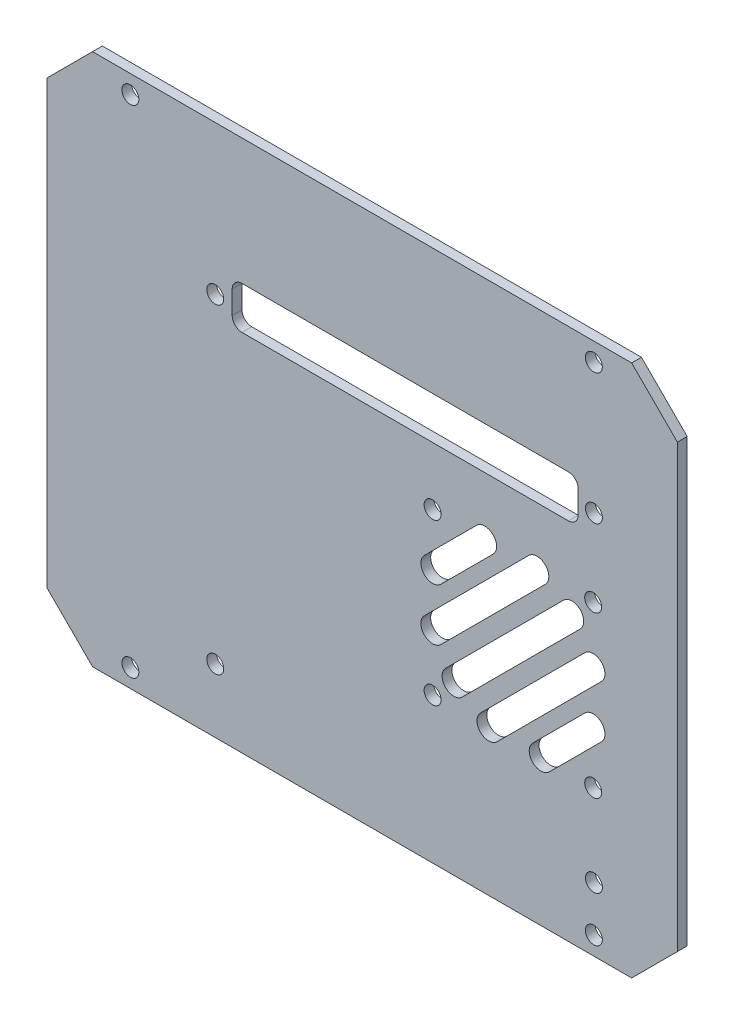
SolidWorks part; units mm, degrees
ref_plane "前视基准面" through (0, 0, 0) normal (0, 0, 1) x (1, 0, 0)
ref_plane "上视基准面" through (0, 0, 0) normal (0, 1, 0) x (1, 0, 0)
ref_plane "右视基准面" through (0, 0, 0) normal (1, 0, 0) x (0, 0, -1)
sketch "草图2" plane through (0, 0, -39.19) normal (0, 0, -1) x (-1, 0, 0)
  line L32 (-47.3467, -34.0538) -> (-40.3426, -41.058)
  line L33 (-40.3426, -41.058) -> (42.2491, -41.058)
  line L34 (42.2491, -41.058) -> (49.2533, -34.0538)
  line L35 (49.2533, -34.0538) -> (49.2533, 33.5378)
  line L36 (49.2533, 33.5378) -> (42.2491, 40.542)
  line L37 (-47.3467, 33.5378) -> (-47.3467, -34.0538)
  line L38 (-40.3426, 40.542) -> (-47.3467, 33.5378)
  line L39 (42.2491, 40.542) -> (-40.3426, 40.542)
  line L40 (-47.3467, -34.0538) -> (-40.3426, -41.058)
  line L41 (-40.3426, -41.058) -> (42.2491, -41.058)
  line L42 (42.2491, -41.058) -> (49.2533, -34.0538)
  line L43 (49.2533, -34.0538) -> (49.2533, 33.5378)
  line L44 (49.2533, 33.5378) -> (42.2491, 40.542)
  line L45 (-47.3467, 33.5378) -> (-47.3467, -34.0538)
  line L46 (-40.3426, 40.542) -> (-47.3467, 33.5378)
  line L47 (42.2491, 40.542) -> (-40.3426, 40.542)
  dimension "D1" = 0.2
extrude "凸台-拉伸1" add sketch "草图2" along normal blind 1.5
sketch "草图3" plane through (0, 0, -40.69) normal (0, 0, -1) x (-1, 0, 0)
  circle A0 centre (-34.5467, -38.258) radius 1.3
  circle A1 centre (36.4533, -38.258) radius 1.3
  circle A2 centre (-34.5467, 37.742) radius 1.3
  circle A3 centre (36.4533, 37.742) radius 1.3
  dimension "D1" = 2.6
extrude "切除-拉伸1" cut sketch "草图3" against normal through all
sketch "草图4" plane through (0, 0, -40.69) normal (0, 0, -1) x (-1, 0, 0)
  circle A1 centre (23.4533, -31.2932) radius 1.3
  circle A2 centre (23.4533, -31.2932) radius 1.3
  circle A3 centre (-34.5583, -31.2932) radius 1.3
  circle A4 centre (-34.5583, -31.2932) radius 1.3
  circle A5 centre (23.4533, 17.742) radius 1.3
  circle A6 centre (23.4533, 17.742) radius 1.3
  circle A7 centre (-34.5583, 17.742) radius 1.3
  circle A8 centre (-34.5583, 17.742) radius 1.3
  dimension "D1" = 0
  dimension "D2" = 0
  dimension "D3" = 0
  dimension "D4" = 0
extrude "切除-拉伸2" cut sketch "草图4" against normal up to next
sketch "草图5" plane through (0, 0, -40.69) normal (0, 0, -1) x (-1, 0, 0)
  line L1 (-32.1467, 14.742) -> (20.8533, 14.742)
  line L2 (-32.1467, 14.742) -> (-32.1467, 21.242)
  line L3 (-32.1467, 21.242) -> (20.8533, 21.242)
  line L4 (20.8533, 14.742) -> (20.8533, 21.242)
  line L7 (-47.3467, 33.5378) -> (-47.3467, -34.0538) construction
  line L9 (42.2491, 40.542) -> (-40.3426, 40.542) construction
  dimension "D1" = 53
  dimension "D2" = 6.5
  dimension "D3" = 15.2
  dimension "D4" = 19.3
extrude "切除-拉伸3" cut sketch "草图5" against normal up to next
fillet "圆角1" radius 1.5 4 edges at (32.1467, 21.242, -39.94) (32.1467, 14.742, -39.94) (-20.8533, 14.742, -39.94) (-20.8533, 21.242, -39.94)
sketch "草图7" plane through (0, 0, -40.69) normal (0, 0, -1) x (-1, 0, 0)
  circle A0 centre (-34.4467, 5.842) radius 1.3
  circle A1 centre (-34.4467, -18.758) radius 1.3
  circle A2 centre (-9.8467, 5.842) radius 1.3
  circle A3 centre (-9.8467, -18.758) radius 1.3
  circle A4 centre (-34.5583, 17.742) radius 1.3 construction
extrude "切除-拉伸4" cut sketch "草图7" against normal up to next
sketch "草图8" plane through (0, 0, -40.69) normal (0, 0, -1) x (-1, 0, 0)
  line L0 (-34.4467, 5.842) -> (-9.8467, -18.758) construction
  line L1 (-34.4467, 5.842) -> (-9.8467, 5.842) construction
  line L2 (-34.4467, 5.842) -> (-34.4467, -18.758) construction
  line L3 (-34.4467, -18.758) -> (-9.8467, -18.758) construction
  line L4 (-9.8467, 5.842) -> (-9.8467, -18.758) construction
  line L5 (-31.194, 2.5893) -> (-13.0994, -15.5053) construction
  line L6 (-29.9212, 3.8621) -> (-11.8266, -14.2325)
  line L7 (-32.4668, 1.3165) -> (-14.3722, -16.7781)
  line L8 (-34.4467, -2.758) -> (-18.4467, -18.758) construction
  line L9 (-33.1739, -1.4852) -> (-17.1739, -17.4852)
  line L10 (-35.7195, -4.0308) -> (-19.7195, -20.0308)
  line L11 (-25.8467, 5.842) -> (-9.8467, -10.158) construction
  line L12 (-24.5739, 7.1148) -> (-8.5739, -8.8852)
  line L13 (-27.1195, 4.5692) -> (-11.1195, -11.4308)
  line L14 (-17.8467, 5.842) -> (-9.8467, -2.158) construction
  line L15 (-16.5739, 7.1148) -> (-8.5739, -0.8852)
  line L16 (-19.1195, 4.5692) -> (-11.1195, -3.4308)
  line L17 (-34.4467, -10.758) -> (-26.4467, -18.758) construction
  line L18 (-33.1739, -9.4852) -> (-25.1739, -17.4852)
  line L19 (-35.7195, -12.0308) -> (-27.7195, -20.0308)
  arc A1 (-29.9212, 3.8621) -> (-32.4668, 1.3165) centre (-31.194, 2.5893) ccw
  arc A2 (-14.3722, -16.7781) -> (-11.8266, -14.2325) centre (-13.0994, -15.5053) ccw
  arc A3 (-33.1739, -1.4852) -> (-35.7195, -4.0308) centre (-34.4467, -2.758) ccw
  arc A4 (-19.7195, -20.0308) -> (-17.1739, -17.4852) centre (-18.4467, -18.758) ccw
  arc A5 (-24.5739, 7.1148) -> (-27.1195, 4.5692) centre (-25.8467, 5.842) ccw
  arc A6 (-11.1195, -11.4308) -> (-8.5739, -8.8852) centre (-9.8467, -10.158) ccw
  arc A7 (-16.5739, 7.1148) -> (-19.1195, 4.5692) centre (-17.8467, 5.842) ccw
  arc A8 (-11.1195, -3.4308) -> (-8.5739, -0.8852) centre (-9.8467, -2.158) ccw
  arc A9 (-33.1739, -9.4852) -> (-35.7195, -12.0308) centre (-34.4467, -10.758) ccw
  arc A10 (-27.7195, -20.0308) -> (-25.1739, -17.4852) centre (-26.4467, -18.758) ccw
  point P10 (-22.1467, -6.458)
  point P15 (-26.4467, -10.758)
  point P22 (-17.8467, -2.158)
  point P29 (-13.8467, 1.842)
  point P36 (-30.4467, -14.758)
  dimension "D1" = 1.8
  dimension "D2" = 1.8
  dimension "D3" = 1.8
  dimension "D4" = 1.8
  dimension "D5" = 1.8
  dimension "D6" = 8
  dimension "D7" = 8
  dimension "D8" = 8
  dimension "D9" = 8
  dimension "D10" = 4.6
  dimension "D11" = 4.6
extrude "切除-拉伸5" cut sketch "草图8" against normal up to next
